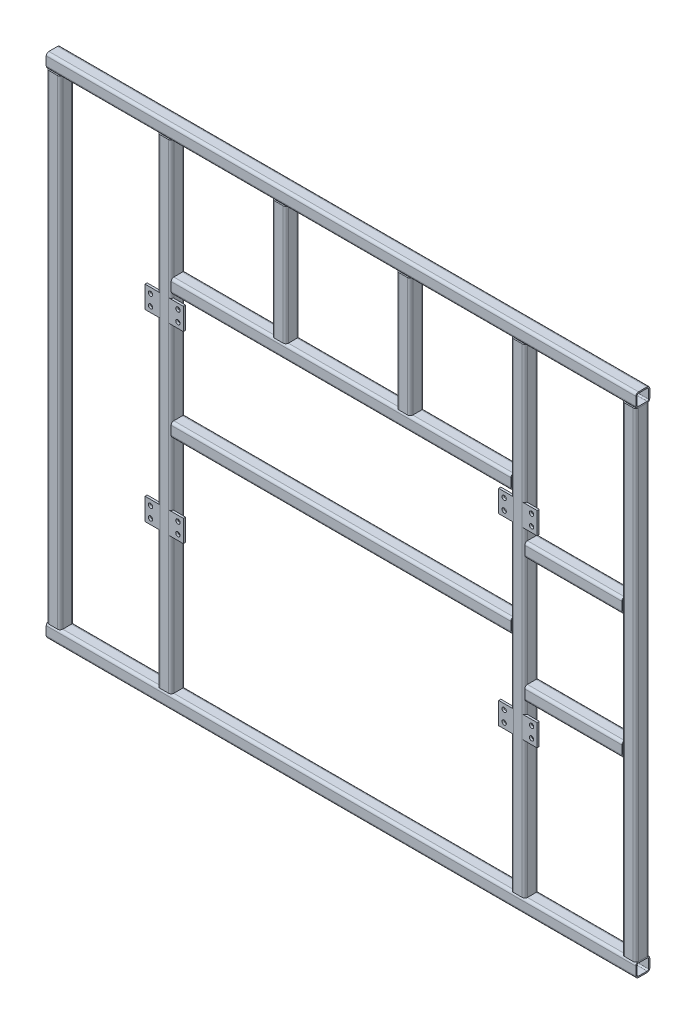
SolidWorks part; units mm, degrees
ref_plane "Płaszczyzna przednia" through (0, 0, 0) normal (0, 0, 1) x (1, 0, 0)
ref_plane "Płaszczyzna górna" through (0, 0, 0) normal (0, 1, 0) x (1, 0, 0)
ref_plane "Płaszczyzna prawa" through (0, 0, 0) normal (1, 0, 0) x (0, 0, -1)
sketch "Szkic1" plane through (0, 0, 0) normal (0, 0, 1) x (1, 0, 0)
  line L0 (405, 1800) -> (405, 0)
  line L1 (0, 0) -> (2100, 0)
  line L2 (0, 0) -> (0, 1800)
  line L3 (0, 1800) -> (2100, 1800)
  line L4 (2100, 0) -> (2100, 1800)
  line L5 (1695, 1800) -> (1695, 0)
  line L6 (1050, 1800) -> (1050, 0) construction
  line L7 (0, 900) -> (2100, 900) construction
  line L8 (1050, 2118.4373) -> (1050, 1514.716) construction
  line L9 (405, 1315) -> (1695, 1315)
  line L10 (405, 861) -> (1695, 861)
  line L11 (1277, 1315) -> (1277, 1800)
  line L12 (823, 1315) -> (823, 1800)
  line L13 (1695, 861) -> (1695, 1315) construction
  line L14 (1695, 1127) -> (2100, 1127)
  line L15 (1695, 673) -> (2100, 673)
  line L16 (1695, 1800) -> (405, 0) construction
  line L17 (405, 1800) -> (1695, 0) construction
  dimension "D1" = 2100
  dimension "D2" = 1800
  dimension "D3" = 1290
  dimension "D4" = 645
  dimension "D5" = 645
  dimension "D6" = 485
  dimension "D8" = 454
  dimension "D9" = 454
  dimension "D7" = 454
other "Rura cienkościenna kwadratowa TS2X2X0.1875(1)"
ref_plane "Płaszczyzna2" through (0, 0, 0) normal (1, 0, 0) x (0, 0, 1)
sketch "Sketch1" plane through (0, 0, 0) normal (1, 0, 0) x (0, 0, 1)
  line L0 (-15.875, -20.6375) -> (15.875, -20.6375)
  line L1 (-20.6375, -15.875) -> (-20.6375, 15.875)
  line L2 (15.875, 20.6375) -> (-15.875, 20.6375)
  line L3 (20.6375, 15.875) -> (20.6375, -15.875)
  line L4 (-15.875, -25.4) -> (15.875, -25.4)
  line L5 (-25.4, -15.875) -> (-25.4, 15.875)
  line L6 (15.875, 25.4) -> (-15.875, 25.4)
  line L7 (25.4, 15.875) -> (25.4, -15.875)
  line L8 (-25.4, 0) -> (-20.6375, 0) construction
  line L9 (-20.6375, 0) -> (20.6375, 0) construction
  line L10 (20.6375, 0) -> (25.4, 0) construction
  line L11 (0, 25.4) -> (0, 20.6375) construction
  line L12 (0, 20.6375) -> (0, -20.6375) construction
  line L13 (0, -20.6375) -> (0, -25.4) construction
  arc A0 (25.4, 15.875) -> (15.875, 25.4) centre (15.875, 15.875) ccw
  arc A1 (15.875, -25.4) -> (25.4, -15.875) centre (15.875, -15.875) ccw
  arc A2 (-25.4, -15.875) -> (-15.875, -25.4) centre (-15.875, -15.875) ccw
  arc A3 (-15.875, 25.4) -> (-25.4, 15.875) centre (-15.875, 15.875) ccw
  arc A4 (-15.875, 20.6375) -> (-20.6375, 15.875) centre (-15.875, 15.875) ccw
  arc A5 (20.6375, 15.875) -> (15.875, 20.6375) centre (15.875, 15.875) ccw
  arc A6 (15.875, -20.6375) -> (20.6375, -15.875) centre (15.875, -15.875) ccw
  arc A7 (-20.6375, -15.875) -> (-15.875, -20.6375) centre (-15.875, -15.875) ccw
  point P6 (-25.4, -25.4)
  point P33 (-25.4, 25.4)
  point P35 (25.4, 25.4)
  point P36 (25.4, -25.4)
  point P37 (0, 0)
  point P38 (0, 0)
  dimension "D1" = 9.525
  dimension "Thickness" = 4.7625
  dimension "V_leg" = 50.8
  dimension "H_leg" = 50.8
sketch "Szkic16" plane through (0, 0, 25.4) normal (0, 0, 1) x (1, 0, 0)
  line L0 (2125.4, 25.4) -> (-25.4, 25.4) construction
  line L1 (1669.6, 1774.6) -> (430.4, 1774.6) construction
  line L2 (1669.6, 1774.6) -> (1669.6, 25.4) construction
  line L3 (1669.6, 25.4) -> (430.4, 25.4) construction
  line L4 (430.4, 1774.6) -> (430.4, 25.4) construction
  line L5 (335, 1275) -> (475, 1275)
  line L6 (335, 1275) -> (335, 1195)
  line L7 (335, 1195) -> (475, 1195)
  line L8 (475, 1275) -> (475, 1195)
  line L9 (335, 1275) -> (475, 1195) construction
  line L10 (335, 1195) -> (475, 1275) construction
  line L11 (1669.6, 1774.6) -> (430.4, 25.4) construction
  line L12 (1669.6, 25.4) -> (430.4, 1774.6) construction
  line L13 (430.4, 1774.6) -> (430.4, 25.4) construction
  circle A0 centre (455, 1255) radius 8
  circle A1 centre (455, 1215) radius 8
  circle A2 centre (355, 1215) radius 8
  circle A3 centre (355, 1255) radius 8
  point P9 (405, 1235)
  point P17 (1050, 900)
  dimension "D3" = 20
  dimension "D5" = 16
  dimension "D1" = 140
  dimension "D2" = 80
  dimension "D4" = 20
  dimension "D7" = 645
  dimension "D8" = 335
  dimension "D6" = 2
extrude "Dodanie-wyciągnięcie1" add sketch "Szkic16" against normal blind 8 separate body
pattern_linear "Szyk liniowy1" count 2 spacing 1290 along (1, 0, 0) count 2 spacing 670 along (0, -1, 0) of "Dodanie-wyciągnięcie1"
